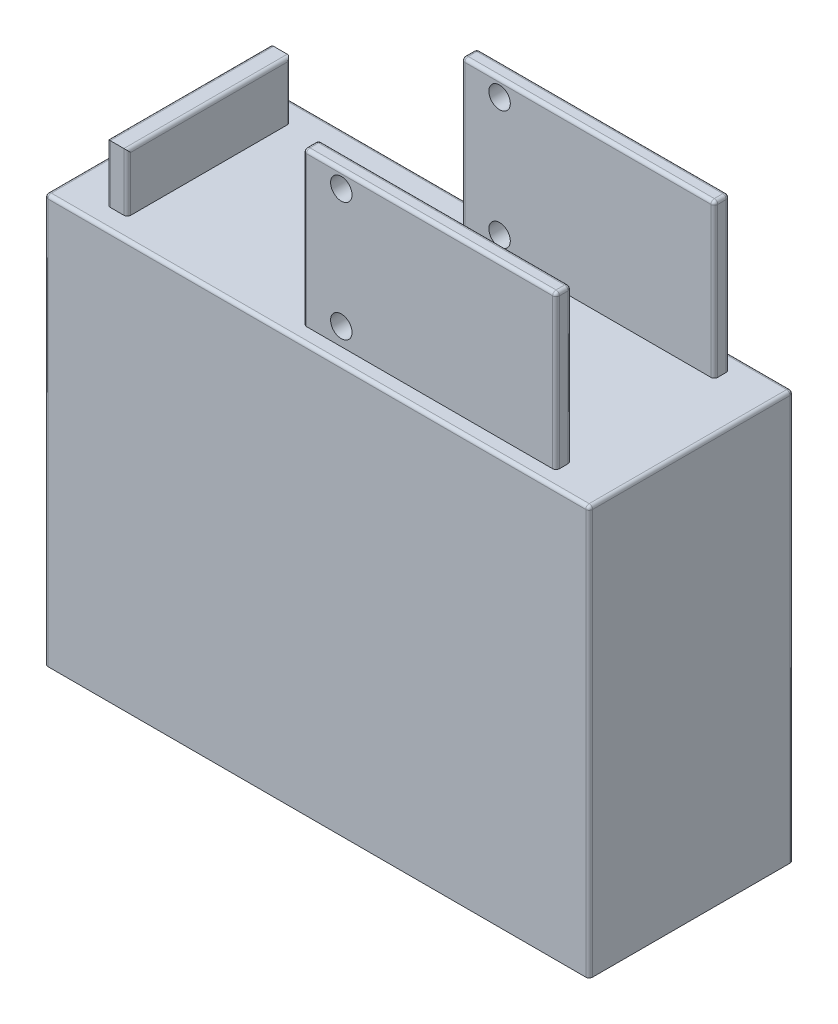
SolidWorks part; units mm, degrees
ref_plane "Front Plane" through (0, 0, 0) normal (0, 0, 1) x (1, 0, 0)
ref_plane "Top Plane" through (0, 0, 0) normal (0, 1, 0) x (1, 0, 0)
ref_plane "Right Plane" through (0, 0, 0) normal (1, 0, 0) x (0, 0, -1)
sketch "Sketch1" plane through (0, 0, 0) normal (0, 0, 1) x (1, 0, 0)
  line L1 (-136.4272, 159.1158) -> (-56.4272, 159.1158)
  line L2 (-136.4272, 159.1158) -> (-136.4272, 99.1158)
  line L3 (-136.4272, 99.1158) -> (-56.4272, 99.1158)
  line L4 (-56.4272, 159.1158) -> (-56.4272, 99.1158)
  dimension "D1" = 60
  dimension "D2" = 80
extrude "Boss-Extrude1" add sketch "Sketch1" along normal blind 30
sketch "Sketch2" plane through (0, 159.1158, 0) normal (0, 1, 0) x (1, 0, 0)
  line L0 (-56.4272, -30) -> (-56.4272, 0) construction
  line L1 (-100.6904, -2.25) -> (-63.5458, -2.25)
  line L2 (-100.6904, -2.25) -> (-100.6904, -4.5)
  line L3 (-100.6904, -4.5) -> (-63.5458, -4.5)
  line L4 (-63.5458, -2.25) -> (-63.5458, -4.5)
  line L5 (-100.6904, -25.5) -> (-63.5458, -25.5)
  line L6 (-100.6904, -25.5) -> (-100.6904, -27.75)
  line L7 (-100.6904, -27.75) -> (-63.5458, -27.75)
  line L8 (-63.5458, -25.5) -> (-63.5458, -27.75)
  line L11 (-56.4272, -30) -> (-136.4272, -30) construction
  line L12 (-56.4272, 0) -> (-136.4272, 0) construction
  dimension "D1" = 44.2632
  dimension "D2" = 2.25
  dimension "D3" = 4.5
  dimension "D4" = 4.5
  dimension "D5" = 2.25
  dimension "D6" = 21
extrude "Boss-Extrude2" add sketch "Sketch2" along normal blind 22.5
sketch "Sketch3" plane through (0, 159.1158, 0) normal (0, 1, 0) x (1, 0, 0)
  line L0 (-136.4272, -30) -> (-136.4272, 0) construction
  line L1 (-130.2772, -3) -> (-127.2772, -3)
  line L2 (-130.2772, -3) -> (-130.2772, -27)
  line L3 (-130.2772, -27) -> (-127.2772, -27)
  line L4 (-127.2772, -3) -> (-127.2772, -27)
  line L5 (-56.4272, 0) -> (-136.4272, 0) construction
  line L6 (-56.4272, -30) -> (-136.4272, -30) construction
  dimension "D1" = 9.15
  dimension "D2" = 3
  dimension "D3" = 3
  dimension "D4" = 3
extrude "Boss-Extrude3" add sketch "Sketch3" along normal blind 8.5
sketch "Sketch5" plane through (0, 0, 2.25) normal (0, 0, -1) x (-1, 0, 0)
  line L0 (100.6904, 181.6158) -> (100.6904, 159.1158) construction
  line L1 (63.5458, 170.3658) -> (100.6904, 170.3658) construction
  line L2 (63.5458, 181.6158) -> (63.5458, 159.1158) construction
  circle A0 centre (95.0904, 161.7158) radius 1.575
  circle A1 centre (95.0904, 179.2158) radius 1.575
  dimension "D2" = 3.15
  dimension "D4" = 3.15
  dimension "D1" = 5.6
  dimension "D3" = 5.6
  dimension "D5" = 17.5
  dimension "D6" = 8.65
extrude "Cut-Extrude1" cut sketch "Sketch5" against normal blind 30
fillet "Fillet2" radius 0.5 30 edges at (-136.4272, 129.1158, 0) (-136.4272, 129.1158, 30) (-56.4272, 129.1158, 30) (-56.4272, 129.1158, 0) (-56.4272, 159.1158, 15) (-96.4272, 159.1158, 30) (-136.4272, 159.1158, 15) (-96.4272, 159.1158, 0) (-130.2772, 163.3658, 27) (-127.2772, 163.3658, 27) (-127.2772, 167.6158, 15) (-130.2772, 167.6158, 15) (-127.2772, 163.3658, 3) (-130.2772, 163.3658, 3) (-100.6904, 170.3658, 25.5) (-100.6904, 170.3658, 27.75) (-100.6904, 181.6158, 26.625) (-82.1181, 181.6158, 27.75) (-63.5458, 181.6158, 26.625) (-63.5458, 170.3658, 27.75) (-63.5458, 170.3658, 25.5) (-63.5458, 181.6158, 3.375) (-100.6904, 181.6158, 3.375) (-82.1181, 181.6158, 25.5) (-63.5458, 170.3658, 4.5) (-63.5458, 170.3658, 2.25) (-82.1181, 181.6158, 4.5) (-100.6904, 170.3658, 4.5) (-100.6904, 170.3658, 2.25) (-82.1181, 181.6158, 2.25)
